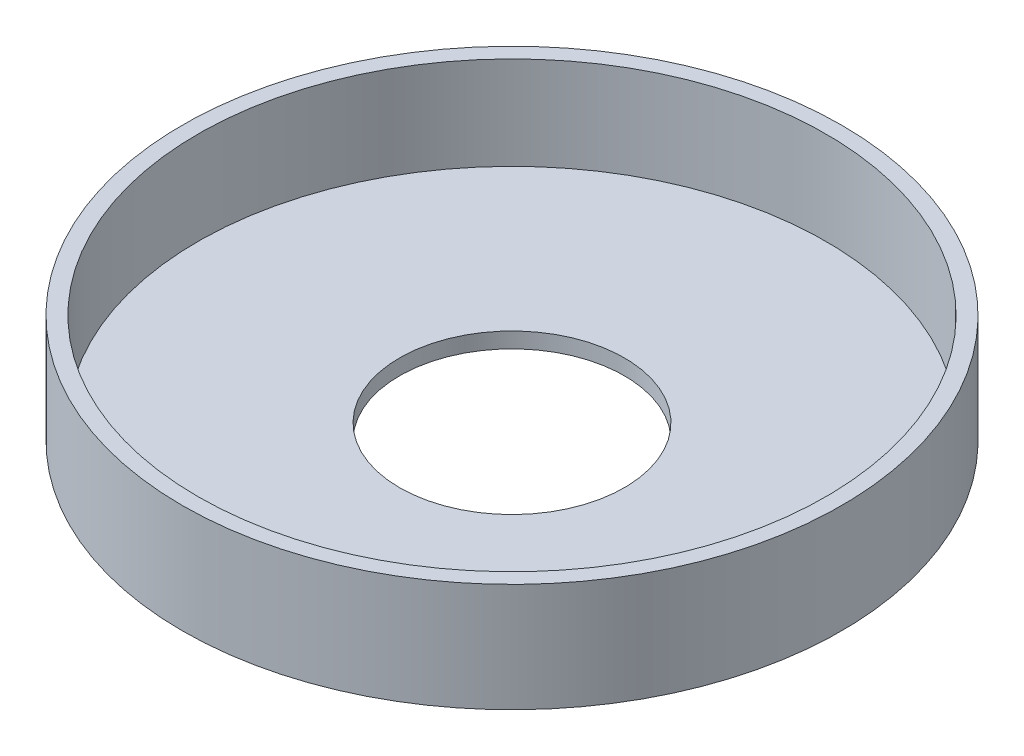
SolidWorks part; units mm, degrees
ref_plane "Front Plane" through (0, 0, 0) normal (0, 0, 1) x (1, 0, 0)
ref_plane "Top Plane" through (0, 0, 0) normal (0, 1, 0) x (1, 0, 0)
ref_plane "Right Plane" through (0, 0, 0) normal (1, 0, 0) x (0, 0, -1)
sketch "Sketch1" plane through (0, 0, 0) normal (0, 1, 0) x (1, 0, 0)
  circle A0 centre (0, 0) radius 14.5
  circle A1 centre (0, 0) radius 42.5
  dimension "D1" = 29
  dimension "D2" = 85
extrude "Boss-Extrude1" add sketch "Sketch1" along normal blind 2
sketch "Sketch2" plane through (0, 2, 0) normal (0, 1, 0) x (1, 0, 0)
  circle A0 centre (0, 0) radius 42.5
  circle A1 centre (0, 0) radius 40.5
  dimension "D1" = 2
  dimension "D2" = 85
extrude "Boss-Extrude2" add sketch "Sketch2" along normal blind 12
